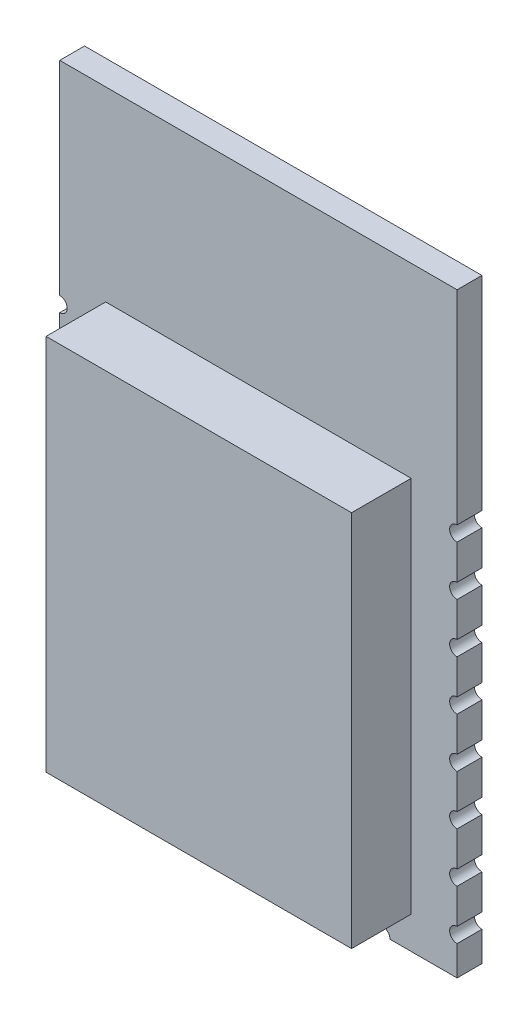
SolidWorks part; units mm, degrees
ref_plane "Front Plane" through (0, 0, 0) normal (0, 0, 1) x (1, 0, 0)
ref_plane "Top Plane" through (0, 0, 0) normal (0, 1, 0) x (1, 0, 0)
ref_plane "Right Plane" through (0, 0, 0) normal (1, 0, 0) x (0, 0, -1)
sketch "Sketch1" plane through (0, 0, 0) normal (0, 0, 1) x (1, 0, 0)
  line L1 (-8, 12) -> (8, 12)
  line L2 (-8, 12) -> (-8, -12)
  line L3 (-8, -12) -> (8, -12)
  line L4 (8, 12) -> (8, -12)
  line L5 (-8, 12) -> (8, -12) construction
  line L6 (-8, -12) -> (8, 12) construction
  point P0 (0, 0)
  dimension "D1" = 24
  dimension "D2" = 16
extrude "Boss-Extrude1" add sketch "Sketch1" along normal blind 1
sketch "Sketch2" plane through (0, 0, 1) normal (0, 0, 1) x (1, 0, 0)
  line L0 (-8, -12) -> (8, -12) construction
  line L1 (-6.15, -10.7) -> (6.15, -10.7)
  line L2 (-6.15, -10.7) -> (-6.15, 4.5)
  line L3 (-6.15, 4.5) -> (6.15, 4.5)
  line L4 (6.15, -10.7) -> (6.15, 4.5)
  line L5 (-6.15, -10.7) -> (6.15, 4.5) construction
  line L6 (-6.15, 4.5) -> (6.15, -10.7) construction
  line L7 (8, 12) -> (-8, 12) construction
  point P0 (0, -3.1)
  point P5 (4.417, 4.6717)
  point P6 (0, -10.7)
  point P9 (0, -12)
  dimension "D1" = 1.3
  dimension "D2" = 7.5
  dimension "D3" = 12.3
extrude "Boss-Extrude2" add sketch "Sketch2" along normal offset from surface (2.4 mm away) 3.4 up to face at (0, 0, 0)
sketch "Sketch3" plane through (0, 0, 0) normal (0, 0, -1) x (-1, 0, 0)
  line L0 (8, 12) -> (8, -12) construction
  line L1 (8, -12) -> (-8, -12) construction
  circle A0 centre (8, -10.5) radius 0.3
  point P4 (8, -10.4308)
  dimension "D2" = 0.6
  dimension "D1" = 1.5
extrude "Cut-Extrude1" cut sketch "Sketch3" against normal through all
pattern_linear "LPattern1" count 8 spacing 2 along (0, 1, 0) of "Cut-Extrude1"
mirror "Mirror1" about plane through (0, 0, 0) normal (1, 0, 0) of "Cut-Extrude1", "LPattern1"
sketch "Sketch4" plane through (0, 0, 0) normal (0, 0, -1) x (-1, 0, 0)
  line L0 (8, -12) -> (-8, -12) construction
  line L1 (8, -10.8) -> (8, -12) construction
  circle A0 centre (5, -12) radius 0.3
  dimension "D1" = 0.6
  dimension "D2" = 3
extrude "Cut-Extrude2" cut sketch "Sketch4" against normal through all
pattern_linear "LPattern2" count 6 spacing 2 along (1, 0, 0) of "Cut-Extrude2"
equation "\"D1@Sketch4\"=\"D2@Sketch3\""
